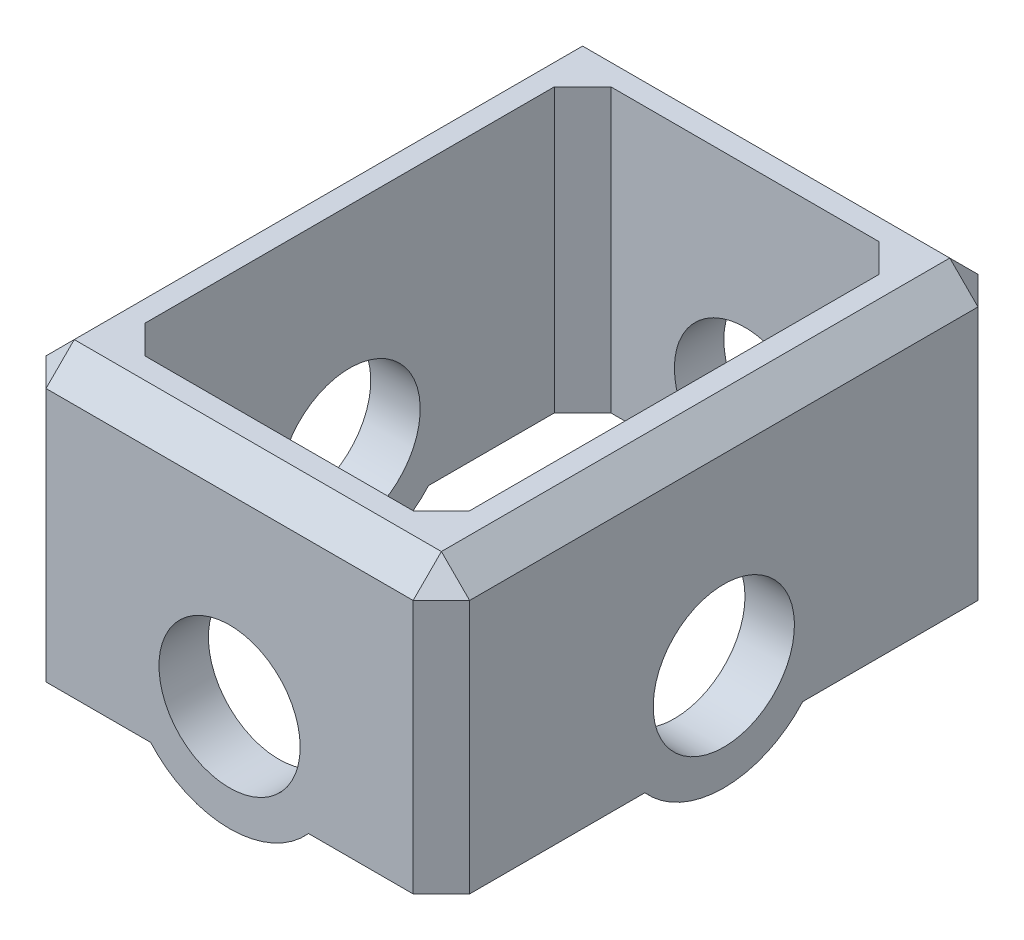
SolidWorks part; units mm, degrees
ref_plane "Front Plane" through (0, 0, 0) normal (0, 0, 1) x (1, 0, 0)
ref_plane "Top Plane" through (0, 0, 0) normal (0, 1, 0) x (1, 0, 0)
ref_plane "Right Plane" through (0, 0, 0) normal (1, 0, 0) x (0, 0, -1)
sketch "Sketch1" plane through (0, 0, 0) normal (0, 0, 1) x (1, 0, 0)
  line L0 (5.5902, -10) -> (-5.5902, -10)
  line L1 (-15, 10) -> (15, 10)
  line L2 (-15, 10) -> (-15, -10)
  line L3 (-15, -10) -> (15, -10)
  line L4 (15, 10) -> (15, -10)
  line L5 (-15, 10) -> (15, -10) construction
  line L6 (-15, -10) -> (15, 10) construction
  line L7 (0, 0) -> (0, -19.9841) construction
  arc A0 (-5.5902, -10) -> (5.5902, -10) centre (0, -5) ccw
  circle A1 centre (0, -5) radius 5
  point P0 (0, 0)
  dimension "D2" = 15
  dimension "D4" = 10
  dimension "D1" = 20
  dimension "D3" = 5
  dimension "D5" = 30
extrude "Boss-Extrude1" add sketch "Sketch1" along normal blind 40 contours L0 L3 A0 | L3 A1 L0 L4 L1 L2
sketch "Sketch3" plane through (0, 10, 0) normal (0, 1, 0) x (1, 0, 0)
  line L18 (-11.5, -36.5) -> (11.5, -36.5)
  line L19 (11.5, -36.5) -> (11.5, -3.5)
  line L20 (-11.5, -3.5) -> (-11.5, -36.5)
  line L21 (11.5, -3.5) -> (-11.5, -3.5)
  line L22 (-11.5, -36.5) -> (11.5, -36.5)
  line L23 (11.5, -36.5) -> (11.5, -3.5)
  line L24 (-11.5, -3.5) -> (-11.5, -36.5)
  line L25 (11.5, -3.5) -> (-11.5, -3.5)
  dimension "D1" = 3.5
extrude "Cut-Extrude1" cut sketch "Sketch3" against normal up to next
sketch "Sketch4" plane through (-15, 0, 0) normal (-1, 0, 0) x (0, 0, 1)
  line L0 (40, -10) -> (0, -10) construction
  line L1 (14.4098, -10) -> (25.5902, -10)
  line L2 (40, 10) -> (0, 10) construction
  arc A0 (14.4098, -10) -> (25.5902, -10) centre (20, -5) ccw
  point P8 (20, 10)
  dimension "D1" = 5
  dimension "D2" = 15
extrude "Boss-Extrude2" add sketch "Sketch4" against normal blind 3.5
sketch "Sketch6" plane through (-15, 0, 0) normal (-1, 0, 0) x (0, 0, 1)
  circle A0 centre (20, -5) radius 5
  dimension "D1" = 10
mirror "Mirror1" about plane through (0, 0, 0) normal (1, 0, 0) of "Boss-Extrude2"
chamfer "Chamfer1" distance 2 angle 45 12 edges at (11.5, 0, 36.5) (-11.5, 0, 36.5) (-11.5, 0, 3.5) (11.5, 0, 3.5) (0, 10, 0) (0, 10, 40) (15, 0, 0) (15, 0, 40) (15, 10, 20) (-15, 0, 0) (-15, 10, 20) (-15, 0, 40)
extrude "Cut-Extrude8" cut sketch "Sketch6" against normal through all
